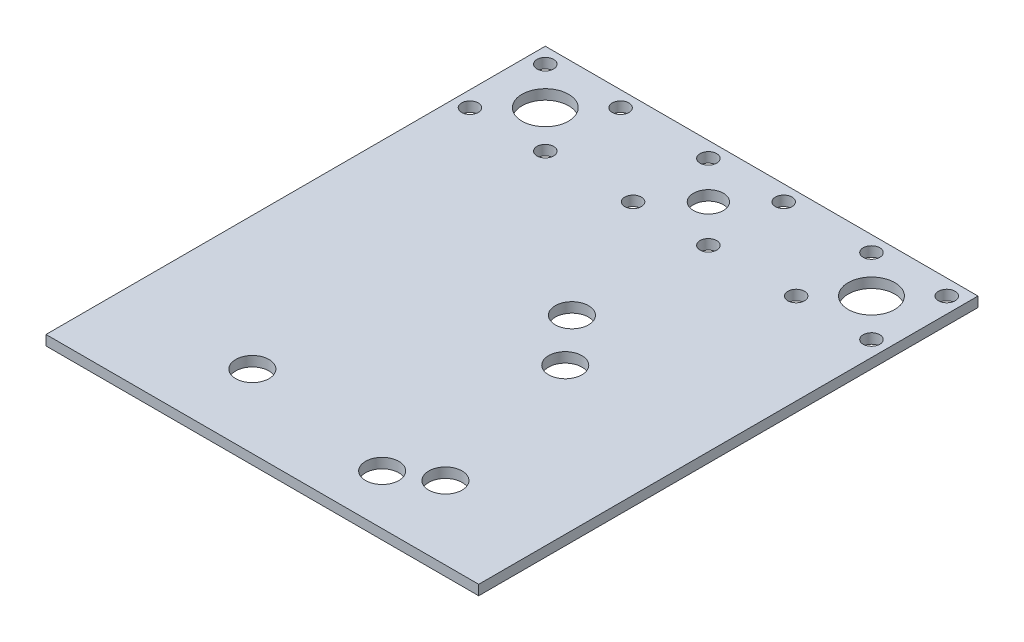
SolidWorks part; units mm, degrees
ref_plane "Front Plane" through (0, 0, 0) normal (0, 0, 1) x (1, 0, 0)
ref_plane "Top Plane" through (0, 0, 0) normal (0, 1, 0) x (1, 0, 0)
ref_plane "Right Plane" through (0, 0, 0) normal (1, 0, 0) x (0, 0, -1)
sketch "Sketch1" plane through (0, 0, 0) normal (0, 1, 0) x (1, 0, 0)
  line L1 (0, 0) -> (130, 0)
  line L2 (0, 0) -> (0, -150)
  line L3 (0, -150) -> (130, -150)
  line L4 (130, 0) -> (130, -150)
  dimension "D1" = 130
  dimension "D2" = 150
extrude "Boss-Extrude1" add sketch "Sketch1" along normal blind 3
hole_wizard "Ø10.0 (10) Diameter Hole2" positions "Sketch3" profile "Sketch2" hole size "Ø10.0" standard "ANSI Metric" end condition through all
sketch "Sketch3" plane through (0, 3, 0) normal (0, 1, 0) x (1, 0, 0)
  point P0 (98, -128)
  point P2 (40, -128)
  point P4 (74, -66)
sketch "Sketch2" plane through (98, 3, 128) normal (1, 0, 0) x (0, 0, 1)
  line L0 (0, 0) -> (0, 3)
  line L1 (0, 3) -> (5, 3)
  line L2 (5, 3) -> (5, 0)
  line L5 (5, 0) -> (0, 0)
  line L11 (0, -6.35) -> (0, 107.95) construction
  dimension "Thru Hole Dia." = 10
  dimension "Thru Hole Depth" = 3
sketch "Sketch4" plane through (0, 0, 0) normal (0, 1, 0) x (1, 0, 0)
  line L0 (4.6863, -27.3137) -> (27.3137, -4.6863) construction
  line L1 (4.6863, -4.6863) -> (27.3137, -4.6863) construction
  line L2 (4.6863, -4.6863) -> (4.6863, -27.3137) construction
  line L3 (4.6863, -27.3137) -> (27.3137, -27.3137) construction
  line L4 (27.3137, -4.6863) -> (27.3137, -27.3137) construction
  line L5 (4.6863, -4.6863) -> (27.3137, -27.3137) construction
  line L6 (130, 0) -> (0, 0) construction
  line L7 (0, 0) -> (0, -150) construction
  line L8 (130, -150) -> (130, 0) construction
  line L9 (102.6863, -4.6863) -> (125.3137, -4.6863) construction
  line L10 (102.6863, -4.6863) -> (102.6863, -27.3137) construction
  line L11 (102.6863, -27.3137) -> (125.3137, -27.3137) construction
  line L12 (125.3137, -4.6863) -> (125.3137, -27.3137) construction
  line L13 (102.6863, -4.6863) -> (125.3137, -27.3137) construction
  line L14 (102.6863, -27.3137) -> (125.3137, -4.6863) construction
  line L15 (16, -16) -> (114, -16) construction
  line L17 (53.6863, -4.6863) -> (76.3137, -4.6863) construction
  line L18 (53.6863, -4.6863) -> (53.6863, -27.3137) construction
  line L19 (53.6863, -27.3137) -> (76.3137, -27.3137) construction
  line L20 (76.3137, -4.6863) -> (76.3137, -27.3137) construction
  line L21 (53.6863, -4.6863) -> (76.3137, -27.3137) construction
  line L22 (53.6863, -27.3137) -> (76.3137, -4.6863) construction
  circle A0 centre (16, -16) radius 16 construction
  circle A1 centre (65, -16) radius 16 construction
  circle A2 centre (114, -16) radius 16 construction
  point P10 (114, -16)
  dimension "D2" = 32
  dimension "D3" = 32
  dimension "D1" = 32
hole_wizard "Ø14.0 (14) Diameter Hole1" positions "Sketch6" profile "Sketch5" hole size "Ø14.0" standard "ANSI Metric" end condition through all
sketch "Sketch6" plane through (0, 3, 0) normal (0, 1, 0) x (1, 0, 0)
  point P0 (16, -16)
  point P2 (114, -16)
sketch "Sketch5" plane through (16, 3, 16) normal (1, 0, 0) x (0, 0, 1)
  line L0 (0, 0) -> (0, 3)
  line L1 (0, 3) -> (7, 3)
  line L2 (7, 3) -> (7, 0)
  line L5 (7, 0) -> (0, 0)
  line L11 (0, -6.35) -> (0, 107.95) construction
  dimension "Thru Hole Dia." = 14
  dimension "Thru Hole Depth" = 3
hole_wizard "Ø5.0 (5) Diameter Hole1" positions "Sketch8" profile "Sketch7" hole size "Ø5.0" standard "ANSI Metric" end condition through all
sketch "Sketch8" plane through (0, 3, 0) normal (0, 1, 0) x (1, 0, 0)
  point P0 (4.6863, -27.3137)
  point P2 (4.6863, -4.6863)
  point P4 (27.3137, -4.6863)
  point P6 (27.3137, -27.3137)
  point P8 (102.6863, -27.3137)
  point P10 (125.3137, -27.3137)
  point P12 (125.3137, -4.6863)
  point P14 (102.6863, -4.6863)
sketch "Sketch7" plane through (4.6863, 3, 27.3137) normal (1, 0, 0) x (0, 0, 1)
  line L0 (0, 0) -> (0, 3)
  line L1 (0, 3) -> (2.5, 3)
  line L2 (2.5, 3) -> (2.5, 0)
  line L5 (2.5, 0) -> (0, 0)
  line L11 (0, -6.35) -> (0, 107.95) construction
  dimension "Thru Hole Dia." = 5
  dimension "Thru Hole Depth" = 3
hole_wizard "Ø10.0 (10) Diameter Hole1" positions "Sketch10" profile "Sketch9" hole size "Ø10.0" standard "ANSI Metric" end condition through all
sketch "Sketch10" plane through (0, 3, 0) normal (0, 1, 0) x (1, 0, 0)
  point P0 (86, -80)
  point P2 (86, -135)
sketch "Sketch9" plane through (86, 3, 80) normal (1, 0, 0) x (0, 0, 1)
  line L0 (0, 0) -> (0, 3)
  line L1 (0, 3) -> (5, 3)
  line L2 (5, 3) -> (5, 0)
  line L5 (5, 0) -> (0, 0)
  line L11 (0, -6.35) -> (0, 107.95) construction
  dimension "Thru Hole Dia." = 10
  dimension "Thru Hole Depth" = 3
hole_wizard "Ø9.0 (9) Diameter Hole1" positions "Sketch12" profile "Sketch11" hole size "Ø9.0" standard "ANSI Metric" end condition through all
sketch "Sketch12" plane through (0, 3, 0) normal (0, 1, 0) x (1, 0, 0)
  point P5 (65, -16)
sketch "Sketch11" plane through (65, 3, 16) normal (1, 0, 0) x (0, 0, 1)
  line L0 (0, 0) -> (0, 3)
  line L1 (0, 3) -> (4.5, 3)
  line L2 (4.5, 3) -> (4.5, 0)
  line L5 (4.5, 0) -> (0, 0)
  line L11 (0, -6.35) -> (0, 107.95) construction
  dimension "Thru Hole Dia." = 9
  dimension "Thru Hole Depth" = 3
hole_wizard "Ø5.0 (5) Diameter Hole2" positions "Sketch14" profile "Sketch13" hole size "Ø5.0" standard "ANSI Metric" end condition through all
sketch "Sketch14" plane through (0, 3, 0) normal (0, 1, 0) x (1, 0, 0)
  point P0 (53.6863, -27.3137)
  point P2 (76.3137, -27.3137)
  point P4 (76.3137, -4.6863)
  point P6 (53.6863, -4.6863)
sketch "Sketch13" plane through (53.6863, 3, 27.3137) normal (1, 0, 0) x (0, 0, 1)
  line L0 (0, 0) -> (0, 3)
  line L1 (0, 3) -> (2.5, 3)
  line L2 (2.5, 3) -> (2.5, 0)
  line L5 (2.5, 0) -> (0, 0)
  line L11 (0, -6.35) -> (0, 107.95) construction
  dimension "Thru Hole Dia." = 5
  dimension "Thru Hole Depth" = 3
equation "\"a\"= 130"
equation "\"b\"= 150"
equation "\"D2@Sketch1\"=\"b\""
equation "\"D1@Sketch1\"=\"a\""
